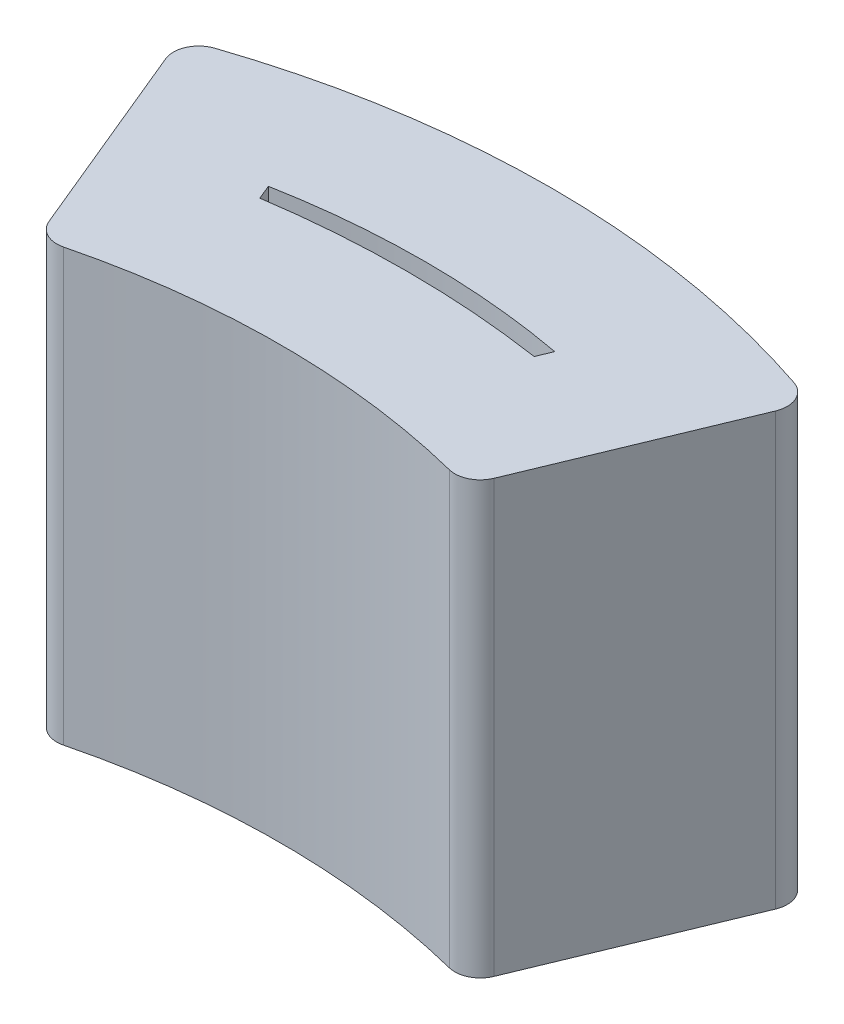
SolidWorks part; units mm, degrees
material "Copper"
ref_plane "Front Plane" through (0, 0, 0) normal (0, 0, 1) x (1, 0, 0)
ref_plane "Top Plane" through (0, 0, 0) normal (0, 1, 0) x (1, 0, 0)
ref_plane "Right Plane" through (0, 0, 0) normal (1, 0, 0) x (0, 0, -1)
sketch "Sketch1" plane through (0, 0, 0) normal (0, 1, 0) x (1, 0, 0)
  line L0 (-44.6154, -35.3811) -> (-68.2462, 21.6687) construction
  line L1 (45.5034, -35.3811) -> (69.1343, 21.6687) construction
  line L2 (-43.3939, -25.2645) -> (-59.645, 13.9693)
  line L3 (44.2819, -25.2645) -> (60.5331, 13.9693)
  line L4 (-26.5794, -0.5301) -> (-27.7676, 2.3385)
  line L5 (27.4675, -0.5301) -> (28.6557, 2.3385)
  line L6 (42.6073, -29.3073) -> (62.5529, 18.8455) construction
  line L7 (-41.7193, -29.3073) -> (-61.6648, 18.8455) construction
  arc A0 (69.1343, 21.6687) -> (-68.2462, 21.6687) centre (0.444, -149.5014) ccw construction
  arc A1 (-44.6154, -35.3811) -> (45.5034, -35.3811) centre (0.444, -179.5014) cw construction
  arc A2 (57.5036, 20.6232) -> (-56.6156, 20.6232) centre (0.444, -149.5014) ccw
  arc A3 (-37.5565, -28.2005) -> (38.4446, -28.2005) centre (0.444, -179.5014) cw
  arc A4 (28.6557, 2.3385) -> (-27.7676, 2.3385) centre (0.444, -149.5014) ccw
  arc A5 (-26.5794, -0.5301) -> (27.4675, -0.5301) centre (0.444, -179.5014) cw
  arc A6 (62.5529, 18.8455) -> (-61.6648, 18.8455) centre (0.444, -149.5014) ccw construction
  arc A7 (60.5331, 13.9693) -> (57.5036, 20.6232) centre (55.9137, 15.8827) ccw
  arc A8 (-41.7193, -29.3073) -> (42.6073, -29.3073) centre (0.444, -179.5014) cw construction
  arc A9 (44.2819, -25.2645) -> (38.4446, -28.2005) centre (39.6625, -23.3511) cw
  arc A10 (-37.5565, -28.2005) -> (-43.3939, -25.2645) centre (-38.7745, -23.3511) cw
  arc A11 (-59.645, 13.9693) -> (-56.6156, 20.6232) centre (-55.0256, 15.8827) cw
  dimension "D3" = 5
  dimension "D1" = 5
  dimension "D2" = 25
extrude "Boss-Extrude1" add sketch "Sketch1" along normal mid plane 85
